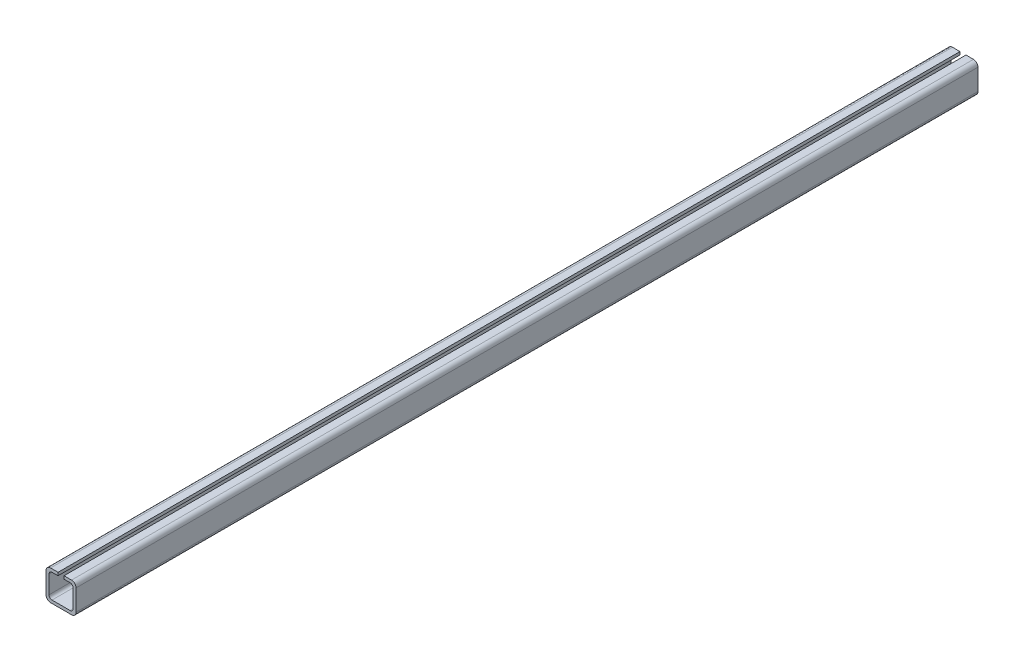
SolidWorks part; units mm, degrees
ref_plane "Płaszczyzna przednia" through (0, 0, 0) normal (0, 0, 1) x (1, 0, 0)
ref_plane "Płaszczyzna górna" through (0, 0, 0) normal (0, 1, 0) x (1, 0, 0)
ref_plane "Płaszczyzna prawa" through (0, 0, 0) normal (1, 0, 0) x (0, 0, -1)
sketch "Szkic1" plane through (0, 0, 0) normal (0, 0, 1) x (1, 0, 0)
  line L0 (-10, -7) -> (-10, 7)
  line L1 (-6, -8) -> (6, -8)
  line L2 (-8, -6) -> (-8, 6)
  line L3 (-6, 8) -> (-2, 8)
  line L4 (8, -6) -> (8, 6)
  line L5 (0, 5.5) -> (0, -8) construction
  line L6 (-8, 0) -> (8, 0) construction
  line L7 (-7, 10) -> (-2, 10)
  line L8 (10, -7) -> (10, 7)
  line L9 (-7, -10) -> (7, -10)
  line L10 (-2, 8) -> (-2, 10)
  line L11 (2, 8) -> (2, 10)
  line L12 (2, 8) -> (6, 8)
  line L13 (-8, 8) -> (8, 8) construction
  line L14 (2, 10) -> (7, 10)
  line L15 (-10, 10) -> (10, 10) construction
  line L16 (10, -10) -> (10, 10) construction
  line L17 (-10, -10) -> (10, -10) construction
  line L18 (-10, -10) -> (-10, 10) construction
  line L19 (8, -8) -> (8, 8) construction
  line L20 (-8, -8) -> (8, -8) construction
  line L21 (-8, -8) -> (-8, 8) construction
  arc A0 (7, 10) -> (10, 7) centre (7, 7) cw
  arc A1 (10, -7) -> (7, -10) centre (7, -7) cw
  arc A2 (-10, -7) -> (-7, -10) centre (-7, -7) ccw
  arc A3 (-10, 7) -> (-7, 10) centre (-7, 7) cw
  arc A4 (6, 8) -> (8, 6) centre (6, 6) cw
  arc A5 (6, -8) -> (8, -6) centre (6, -6) ccw
  arc A6 (-6, -8) -> (-8, -6) centre (-6, -6) cw
  arc A7 (-8, 6) -> (-6, 8) centre (-6, 6) cw
  point P0 (0, 0)
  dimension "D5" = 3
  dimension "D6" = 2
  dimension "D2" = 20
  dimension "D3" = 20
  dimension "D4" = 4
  dimension "D1" = 2
extrude "Dodanie-wyciągnięcie1" add sketch "Szkic1" along normal blind 600
